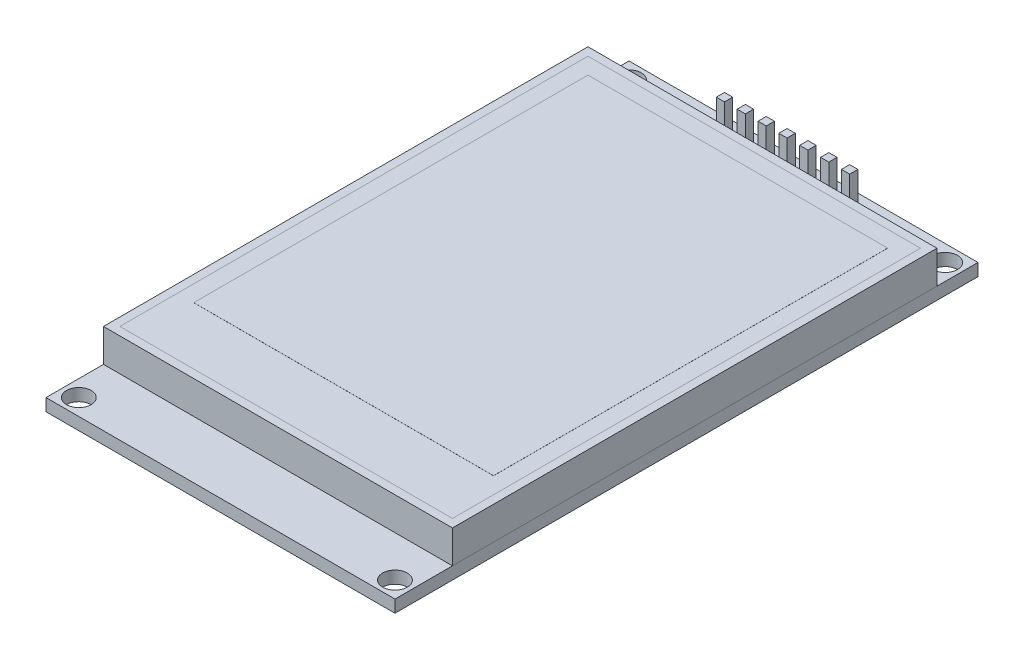
SolidWorks part; units mm, degrees
material "ABS"
ref_plane "Front Plane" through (0, 0, 0) normal (0, 0, 1) x (1, 0, 0)
ref_plane "Top Plane" through (0, 0, 0) normal (0, 1, 0) x (1, 0, 0)
ref_plane "Right Plane" through (0, 0, 0) normal (1, 0, 0) x (0, 0, -1)
sketch "Sketch1" plane through (0, 0, 0) normal (0, 1, 0) x (1, 0, 0)
  line L1 (-21.25, 35.5) -> (21.25, 35.5)
  line L2 (-21.25, 35.5) -> (-21.25, -35.5)
  line L3 (-21.25, -35.5) -> (21.25, -35.5)
  line L4 (21.25, 35.5) -> (21.25, -35.5)
  line L5 (0, -35.5) -> (0, 35.5) construction
  line L6 (-21.25, 0) -> (21.25, 0) construction
  point P0 (0, 0)
  dimension "D1" = 42.5
  dimension "D2" = 71
extrude "Boss-Extrude1" add sketch "Sketch1" along normal blind 1.5
sketch "Sketch7" plane through (0, 1.5, 0) normal (0, 1, 0) x (1, 0, 0)
  line L0 (-21.25, 35.5) -> (21.25, 35.5) construction
  line L1 (-21.25, 35.5) -> (-21.25, -35.5) construction
  circle A0 centre (-19.25, 33.5) radius 1.5
  point P2 (-17.5937, 32.0677)
  dimension "D1" = 3
  dimension "D2" = 2
  dimension "D3" = 2
extrude "Cut-Extrude2" cut sketch "Sketch7" against normal through all
mirror "Mirror1" about plane through (0, 0, 0) normal (0, 0, 1) of "Cut-Extrude2" second plane through (0, 0, 0) second plane normal (1, 0, 0)
sketch "Sketch8" plane through (0, 1.5, 0) normal (0, 1, 0) x (1, 0, 0)
  line L0 (0, -10.821) -> (0, 10.821) construction
  line L1 (-0.5, 34) -> (0.5, 34)
  line L2 (-0.5, 34) -> (-0.5, 33)
  line L3 (-0.5, 33) -> (0.5, 33)
  line L4 (0.5, 34) -> (0.5, 33)
  line L5 (0, 33) -> (0, 34) construction
  line L6 (-0.5, 33.5) -> (0.5, 33.5) construction
  line L7 (-21.25, 35.5) -> (21.25, 35.5) construction
  point P0 (0, 33.5)
  dimension "D1" = 2
  dimension "D2" = 1
extrude "Boss-Extrude5" add sketch "Sketch8" along normal blind 4 and the other way blind 8
pattern_linear "LPattern1" count 4 spacing 2.54 along (1, 0, 0) count 4 spacing 2.54 along (-1, 0, 0) of "Boss-Extrude5"
sketch "Sketch2" plane through (0, 1.5, 0) normal (0, 1, 0) x (1, 0, 0)
  line L1 (-21.25, 30.5) -> (21.25, 30.5)
  line L2 (-21.25, 30.5) -> (-21.25, -28.5)
  line L3 (-21.25, -28.5) -> (21.25, -28.5)
  line L4 (21.25, 30.5) -> (21.25, -28.5)
  line L6 (-21.25, 35.5) -> (-21.25, -35.5) construction
  line L7 (21.25, 35.5) -> (21.25, -35.5) construction
  line L8 (-21.25, 35.5) -> (21.25, 35.5) construction
  line L9 (-21.25, -35.5) -> (21.25, -35.5) construction
  line L10 (-21.25, 1) -> (21.25, 1) construction
  point P4 (0, 1)
  dimension "D1" = 5
  dimension "D2" = 7
extrude "Boss-Extrude2" add sketch "Sketch2" along normal blind 4 separate body
sketch "Sketch3" plane through (0, 5.5, 0) normal (0, 1, 0) x (1, 0, 0)
  line L1 (-20.25, 29.5) -> (20.25, 29.5)
  line L2 (-20.25, 29.5) -> (-20.25, -27.5)
  line L3 (-20.25, -27.5) -> (20.25, -27.5)
  line L4 (20.25, 29.5) -> (20.25, -27.5)
  line L5 (0, -10.821) -> (0, 10.821) construction
  line L6 (-21.25, 30.5) -> (21.25, 30.5) construction
  line L7 (-21.25, 35.5) -> (-21.25, -35.5) construction
  line L9 (-21.25, 1) -> (21.25, 1) construction
  point P5 (19.1922, -25.3803)
  point P8 (0, 29.5)
  point P12 (-20.25, 1)
  dimension "D1" = 1
  dimension "D2" = 1
extrude "Cut-Extrude1" cut sketch "Sketch3" against normal through all
sketch "Sketch5" plane through (0, 1.5, 0) normal (0, 1, 0) x (1, 0, 0)
  line L4 (20.25, 29.5) -> (-20.25, 29.5)
  line L5 (20.25, -27.5) -> (20.25, 29.5)
  line L6 (-20.25, -27.5) -> (20.25, -27.5)
  line L7 (-20.25, 29.5) -> (-20.25, -27.5)
  line L8 (20.25, 29.5) -> (-20.25, 29.5)
  line L9 (20.25, -27.5) -> (20.25, 29.5)
  line L10 (-20.25, -27.5) -> (20.25, -27.5)
  line L11 (-20.25, 29.5) -> (-20.25, -27.5)
  dimension "D1" = 0
extrude "Boss-Extrude3" add sketch "Sketch5" along normal up to surface (4 mm away) separate body up to face at (0, 5.5, -1)
sketch "Sketch6" plane through (0, 5.5, 0) normal (0, 1, 0) x (1, 0, 0)
  line L0 (0, -10.821) -> (0, 10.821) construction
  line L1 (-18.25, 27.5) -> (18.25, 27.5)
  line L2 (-18.25, 27.5) -> (-18.25, -20.5)
  line L3 (-18.25, -20.5) -> (18.25, -20.5)
  line L4 (18.25, 27.5) -> (18.25, -20.5)
  line L6 (-20.25, 29.5) -> (20.25, 29.5) construction
  line L7 (-20.25, 29.5) -> (-20.25, -27.5) construction
  line L8 (-20.25, -27.5) -> (20.25, -27.5) construction
  line L9 (-21.25, 35.5) -> (21.25, 35.5) construction
  line L10 (-21.25, 35.5) -> (-21.25, -35.5) construction
  line L11 (-21.25, -35.5) -> (21.25, -35.5) construction
  point P4 (0, 27.5)
  point P7 (-18.25, -20.0931)
  point P10 (-18.2709, 26.9031)
  dimension "D1" = 2
  dimension "D2" = 2
  dimension "D3" = 7
  dimension "D4" = 8
  dimension "D5" = 3
  dimension "D6" = 15
extrude "Boss-Extrude4" add sketch "Sketch6" along normal blind 0.01
